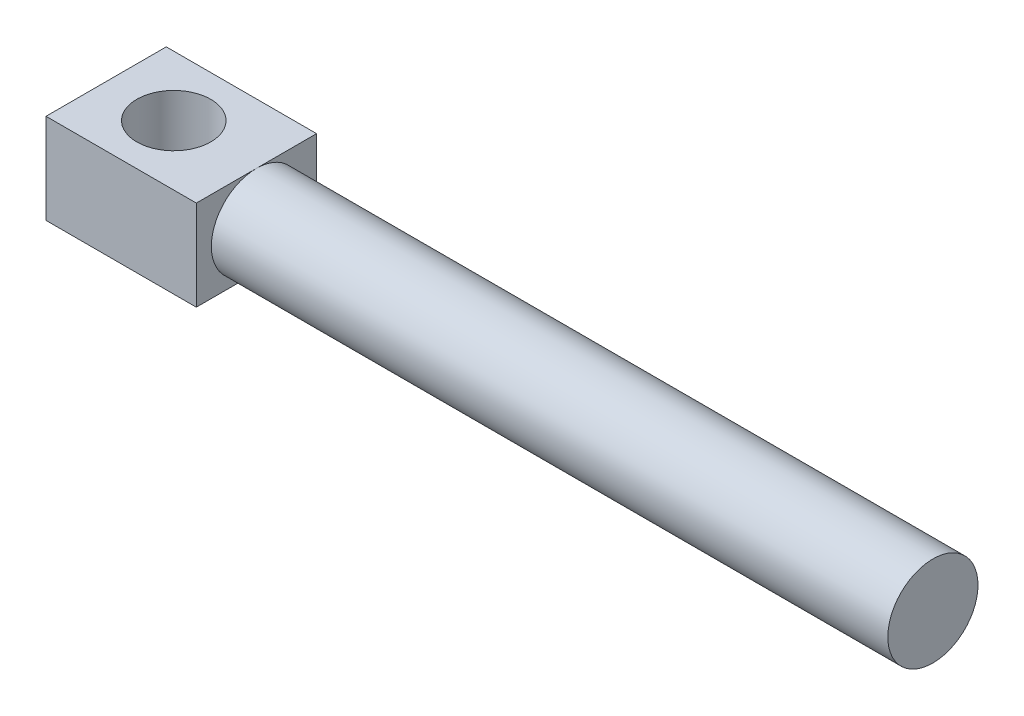
SolidWorks part; units mm, degrees
ref_plane "前视基准面" through (0, 0, 0) normal (0, 0, 1) x (1, 0, 0)
ref_plane "上视基准面" through (0, 0, 0) normal (0, 1, 0) x (1, 0, 0)
ref_plane "右视基准面" through (0, 0, 0) normal (1, 0, 0) x (0, 0, -1)
other "Configuration Table"
sketch "草图1" plane through (0, 0, 0) normal (0, 1, 0) x (1, 0, 0)
  line L1 (-5, 4) -> (5, 4)
  line L2 (-5, 4) -> (-5, -4)
  line L3 (-5, -4) -> (5, -4)
  line L4 (5, 4) -> (5, -4)
  line L5 (0, -4) -> (0, 4) construction
  line L6 (-5, 0) -> (5, 0) construction
  point P0 (0, 0)
  dimension "D1" = 8
  dimension "D2" = 10
extrude "凸台-拉伸1" add sketch "草图1" along normal blind 6
sketch "草图2" plane through (5, 0, 0) normal (1, 0, 0) x (0, 0, -1)
  line L3 (0, 0) -> (0, 6)
  line L4 (-4, 6) -> (4, 6) construction
  circle A0 centre (0, 3) radius 3
  point P3 (0, 3)
  dimension "D1" = 6
extrude "凸台-拉伸2" add sketch "草图2" along normal blind 45 contours L3 A0 | L3 A0
sketch "草图3" plane through (0, 6, 0) normal (0, 1, 0) x (1, 0, 0)
  circle A0 centre (-0.5, 0) radius 2.46
  point P2 (0, 0)
  dimension "D1" = 4.92
  dimension "D2" = 0.5
extrude "切除-拉伸1" cut sketch "草图3" against normal up to next
